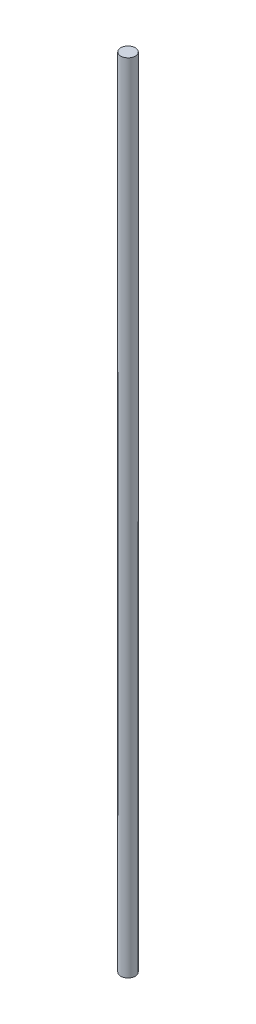
SolidWorks part; units mm, degrees
material "201 Annealed Stainless Steel (SS)"
ref_plane "Front Plane" through (0, 0, 0) normal (0, 0, 1) x (1, 0, 0)
ref_plane "Top Plane" through (0, 0, 0) normal (0, 1, 0) x (1, 0, 0)
ref_plane "Right Plane" through (0, 0, 0) normal (1, 0, 0) x (0, 0, -1)
sketch "Sketch1" plane through (0, 0, 0) normal (0, 1, 0) x (1, 0, 0)
  circle A0 centre (0, 0) radius 4
  dimension "D1" = 8
extrude "Boss-Extrude1" add sketch "Sketch1" along normal blind 439.1
